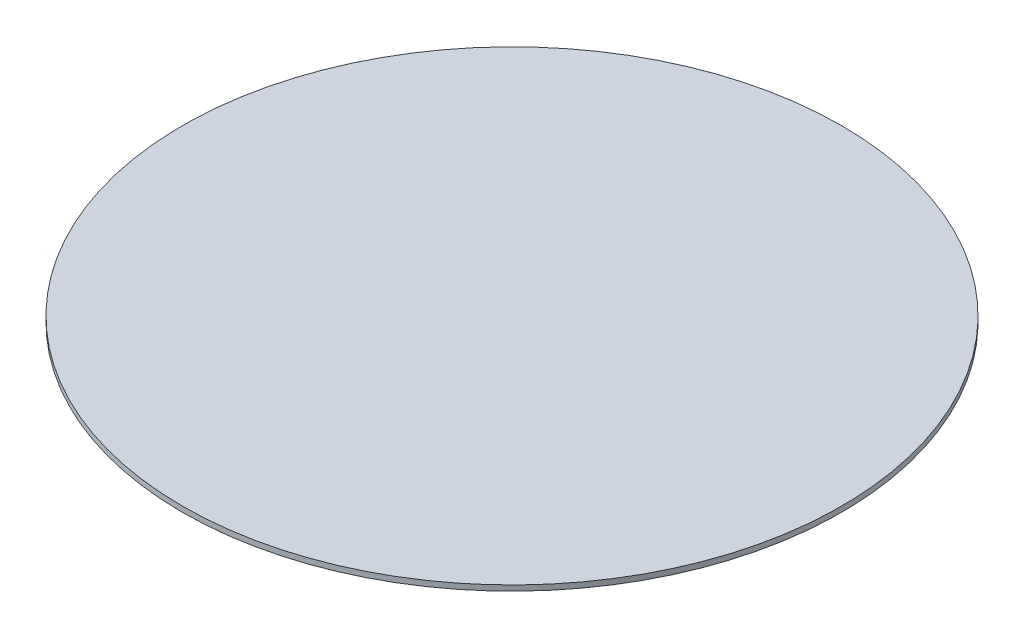
SolidWorks part; units mm, degrees
ref_plane "Front Plane" through (0, 0, 0) normal (0, 0, 1) x (1, 0, 0)
ref_plane "Top Plane" through (0, 0, 0) normal (0, 1, 0) x (1, 0, 0)
ref_plane "Right Plane" through (0, 0, 0) normal (1, 0, 0) x (0, 0, -1)
sketch "Sketch1" plane through (0, 0, 0) normal (0, 1, 0) x (1, 0, 0)
  circle A0 centre (0, 0) radius 609.6
  dimension "D1" = 1219.2
extrude "Boss-Extrude1" add sketch "Sketch1" along normal blind 10
sketch "Sketch2" plane through (0, 10, 0) normal (0, 1, 0) x (1, 0, 0)
  line L0 (0, 0) -> (609.6, 0)
  line L1 (0, 0) -> (304.8, -527.9291)
  line L2 (0, 0) -> (-304.8, -527.9291)
  line L3 (0, 0) -> (-609.6, 0)
  line L4 (0, 0) -> (-304.8, 527.9291)
  line L5 (0, 0) -> (304.8, 527.9291)
  line L6 (-350.5704, 498.7109) -> (-29.6755, 0)
  line L7 (-29.6755, 0) -> (-333.3859, -510.3587)
  line L8 (332.0584, 511.2234) -> (37.6006, 0)
  line L9 (37.6006, 0) -> (332.0584, -511.2234)
  circle A0 centre (0, 0) radius 609.6 construction
  point P13 (0, 0)
  point P18 (-29.6755, 0)
  point P20 (0, 0)
  dimension "D1" = 6
